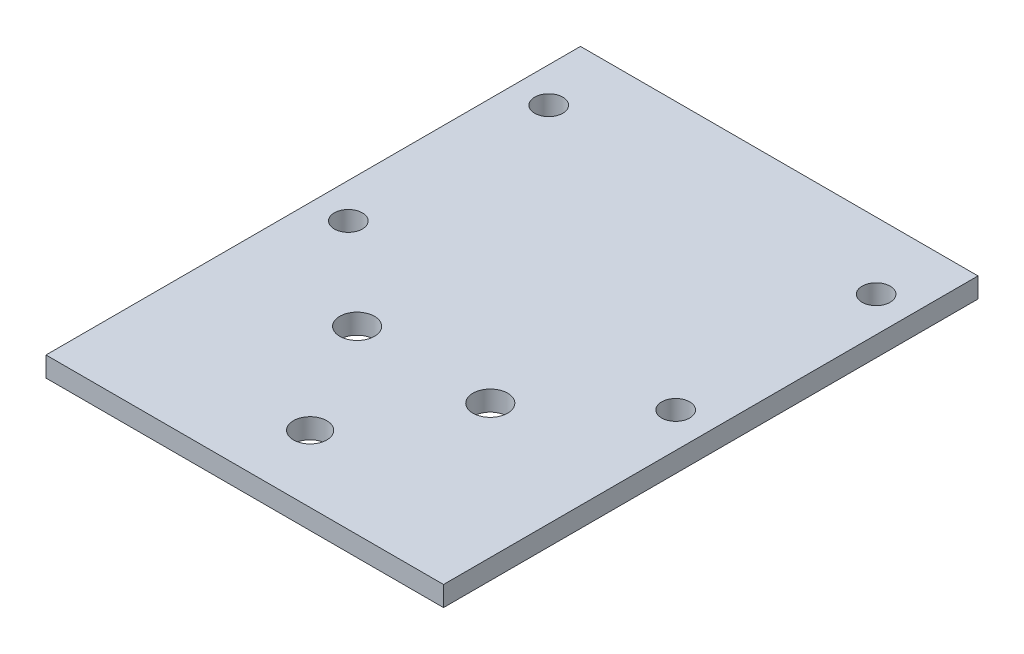
SolidWorks part; units mm, degrees
ref_plane "Front Plane" through (0, 0, 0) normal (0, 0, 1) x (1, 0, 0)
ref_plane "Top Plane" through (0, 0, 0) normal (0, 1, 0) x (1, 0, 0)
ref_plane "Right Plane" through (0, 0, 0) normal (1, 0, 0) x (0, 0, -1)
sketch "Sketch1" plane through (0, 0, 0) normal (0, 1, 0) x (1, 0, 0)
  line L0 (0, 65.7304) -> (0, 15.8737) construction
  line L1 (-29.75, 40) -> (29.75, 40)
  line L2 (-29.75, 40) -> (-29.75, -40)
  line L3 (-29.75, -40) -> (29.75, -40)
  line L4 (29.75, 40) -> (29.75, -40)
  line L5 (-29.75, 40) -> (29.75, -40) construction
  line L6 (-29.75, -40) -> (29.75, 40) construction
  line L7 (68.7213, 15) -> (-100.5795, 15) construction
  circle A0 centre (24.5, 30) radius 2.1
  circle A1 centre (-24.5, 30) radius 2.1
  circle A2 centre (-24.5, 0) radius 2.1
  circle A3 centre (24.5, 0) radius 2.1
  circle A4 centre (9.75, -13) radius 2.6
  circle A5 centre (-10.1825, -13) radius 2.6
  point P0 (0, 0)
  dimension "D3" = 5.25
  dimension "D4" = 4.2
  dimension "D5" = 10
  dimension "D8" = 5.2
  dimension "D1" = 80
  dimension "D2" = 59.5
  dimension "D6" = 29.75
  dimension "D7" = 25
extrude "Boss-Extrude1" add sketch "Sketch1" along normal blind 3
sketch "Sketch2" plane through (0, 0, 0) normal (0, -1, 0) x (1, 0, 0)
  circle A0 centre (-0.2163, 30) radius 2.5
  dimension "D1" = 5
extrude "Cut-Extrude1" cut sketch "Sketch2" against normal blind 10
